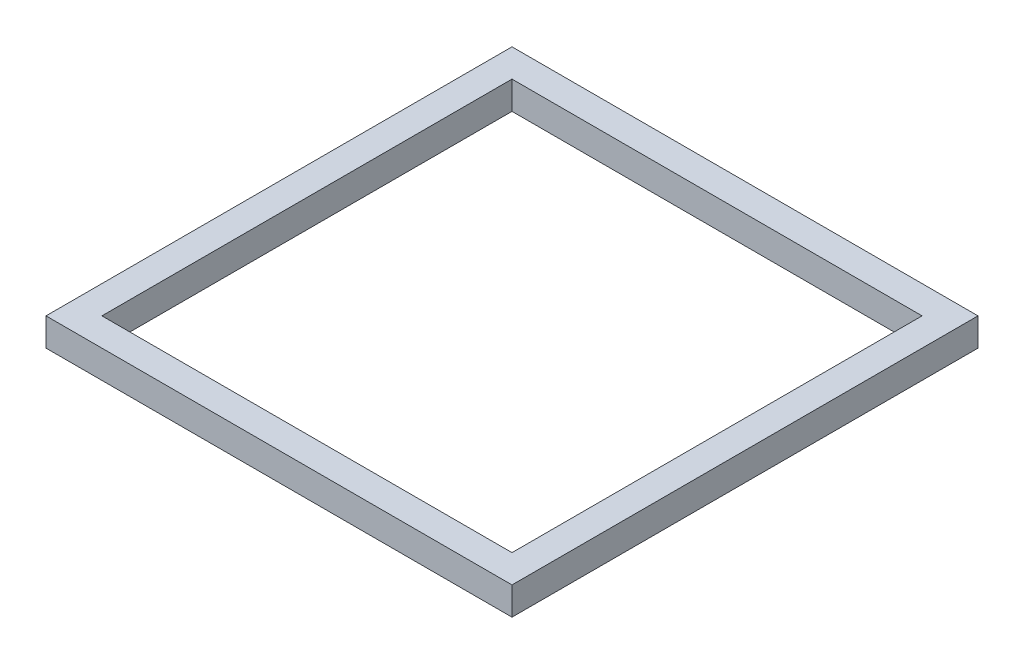
SolidWorks part; units mm, degrees
ref_plane "Front Plane" through (0, 0, 0) normal (0, 0, 1) x (1, 0, 0)
ref_plane "Top Plane" through (0, 0, 0) normal (0, 1, 0) x (1, 0, 0)
ref_plane "Right Plane" through (0, 0, 0) normal (1, 0, 0) x (0, 0, -1)
sketch "Sketch1" plane through (0, 0, 0) normal (0, 1, 0) x (1, 0, 0)
  line L0 (-220, 220) -> (220, 220)
  line L1 (-250, -250) -> (250, -250)
  line L2 (-250, -250) -> (-250, 250)
  line L3 (-250, 250) -> (250, 250)
  line L4 (250, -250) -> (250, 250)
  line L5 (-250, -250) -> (250, 250) construction
  line L6 (-250, 250) -> (250, -250) construction
  line L7 (220, -220) -> (220, 220)
  line L8 (-220, -220) -> (220, -220)
  line L9 (-220, -220) -> (-220, 220)
  point P0 (0, 0)
  dimension "D2" = 500
  dimension "D1" = 30
extrude "Boss-Extrude1" add sketch "Sketch1" along normal blind 30
